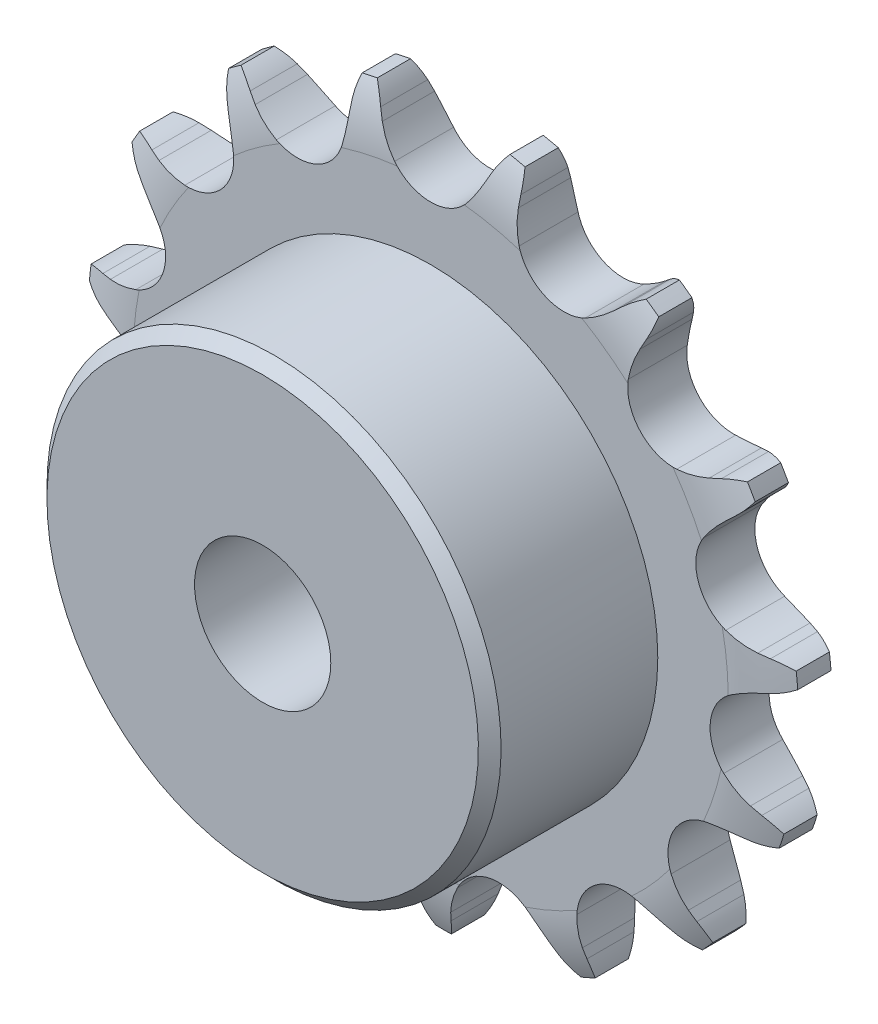
SolidWorks part; units mm, degrees
ref_plane "Front Plane" through (0, 0, 0) normal (0, 0, 1) x (1, 0, 0)
ref_plane "Top Plane" through (0, 0, 0) normal (0, 1, 0) x (1, 0, 0)
ref_plane "Right Plane" through (0, 0, 0) normal (1, 0, 0) x (0, 0, -1)
sketch "Sketch0" plane through (0, 0, 0) normal (0, 0, 1) x (1, 0, 0)
  line L0 (3, -14.1139) -> (0, 0) construction
  line L1 (0, 0) -> (8.4813, -11.6735) construction
  line L2 (0, 0) -> (-3, -14.1139) construction
  line L3 (3, -14.1139) -> (8.4813, -11.6735) construction
  line L4 (3, -14.1139) -> (-3, -14.1139) construction
  line L5 (5.4587, -13.8191) -> (5.1921, -13.4619)
  line L6 (3, -14.1139) -> (0, -14.7516) construction
  line L7 (0.6339, -14.8447) -> (0.7322, -14.4099)
  line L8 (0, -14.1139) -> (0, -15.9139) construction
  line L9 (4.2889, -12.5222) -> (0.9862, -16.6008) construction
  line L10 (0, 0) -> (0, -14.1139) construction
  line L11 (5.1921, -13.4619) -> (0.9862, -16.6008) construction
  line L12 (0, -15.9139) -> (0, -16.1712) construction
  line L13 (8.1159, -11.8362) -> (5.4587, -13.8191) construction
  circle A0 centre (0, 0) radius 15.9139 construction
  circle A1 centre (0, 0) radius 14.4292 construction
  arc A2 (-3.2007, -17.3745) -> (9.9908, -14.5706) centre (0, 0) ccw
  circle A3 centre (0, 0) radius 16.1712 construction
  circle A4 centre (3, -14.1139) radius 2 construction
  arc A7 (4.2889, -12.5222) -> (1.1751, -13.1841) centre (3, -14.1139) ccw
  circle A8 centre (3, -14.1139) radius 2.0481 construction
  arc A9 (5.4587, -13.8191) -> (9.9908, -14.5706) centre (8.1159, -11.8362) ccw
  arc A10 (5.1921, -13.4619) -> (4.2889, -12.5222) centre (0.9862, -16.6008) ccw
  arc A11 (0.6339, -14.8447) -> (-3.2007, -17.3745) centre (-2.6, -14.1139) cw
  arc A12 (0.7322, -14.4099) -> (1.1751, -13.1841) centre (5.8512, -15.5667) cw
  dimension "D1" = 2.0481
  dimension "R" = 2.0481
sketch "Sketch1" plane through (0, 0, 0) normal (1, 0, 0) x (0, 0, -1)
  line L0 (1.3, 0) -> (-1.3, 0)
  line L1 (-1.3, 0) -> (-1.3, 13.1014)
  line L2 (-1.3, 14.4292) -> (0, 14.4292) construction
  line L3 (-0.6, 15.9139) -> (0.6, 15.9139)
  line L5 (1.3, 13.1014) -> (1.3, 0)
  line L7 (0, 15.9139) -> (0, 0) construction
  line L8 (-1.3, 13.1014) -> (1.3, 13.1014) construction
  line L9 (0, 15.9139) -> (0, -15.9139) construction
  line L10 (-1.3, 13.1014) -> (-1.3, 15.9139) construction
  line L11 (-1.3, 15.9139) -> (-0.6, 15.9139) construction
  line L12 (0.6, 15.9139) -> (1.3, 15.9139) construction
  line L13 (1.3, 15.9139) -> (1.3, 13.1014) construction
  line L14 (0, 0) -> (-6.4008, 0) construction
  line L15 (-1.3, 14.4292) -> (-1.3, 10.3292) construction
  line L22 (1.3, 0) -> (-8.7, 0) construction
  line L24 (-1.3, 0) -> (-1.3, 10.3292) construction
  arc A0 (-0.6, 15.9139) -> (-1.3, 13.1014) centre (4.7, 13.1014) ccw
  arc A1 (0.6, 15.9139) -> (1.3, 13.1014) centre (-4.7, 13.1014) cw
  dimension "R" = 6
revolve "Revolve1" add sketch "Sketch1" angle 360 mid plane about L0
extrude "Cut-Extrude1" cut sketch "Sketch0" against normal through all and the other way through all
pattern_circular "CirPattern1" count 15 over 360 about axis through (0, 0, 0) along (0, 0, 1) of "Cut-Extrude1"
sketch "Sketch2" plane through (0, 0, 0) normal (0, 0, 1) x (1, 0, 0)
  circle A0 centre (0, 0) radius 3 construction
  circle A1 centre (0, 0) radius 10
  circle A2 centre (0, 0) radius 15.65 construction
  dimension "Bore" = 6
  dimension "Hub Dia." = 20
  dimension "OD" = 31.3
extrude "Boss-Extrude1" add sketch "Sketch2" along normal up to vertex (8.7 mm away) from surface at 1.3 starting at face at (0, 0, 1.3)
sketch "Sketch3" plane through (0, 0, 0) normal (0, 0, 1) x (1, 0, 0)
  circle A0 centre (0, 0) radius 3 construction
  circle A1 centre (0, 0) radius 3
extrude "Cut-Extrude2" cut sketch "Sketch3" along normal through all and the other way through all
sketch "Sketch4" plane through (0, 0, 0) normal (1, 0, 0) x (0, 0, -1)
  line L0 (-8.7, 10) -> (-8.7, 9.5)
  line L1 (-1.3, 15.9139) -> (-3.25, 15.9139)
  line L2 (-1.3, 15.9139) -> (-1.3, 10.3292)
  line L3 (-1.3, 10.3292) -> (-3.25, 10.3292)
  line L4 (-3.25, 15.9139) -> (-3.25, 10.3292)
  line L9 (-8.7, 9.5) -> (-8.2, 10)
  line L10 (-8.2, 10) -> (-8.7, 10)
  dimension "C" = 0.5
  dimension "D3" = 1.95
revolve "Cut-Revolve1" cut sketch "Sketch4" angle 360 mid plane about L22
sketch "Sketch5" plane through (0, 0, 0) normal (0, 0, 1) x (1, 0, 0)
  circle A0 centre (0, 0) radius 15.65 construction
  circle A1 centre (0, 0) radius 15.65
extrude "Cut-Extrude3" cut sketch "Sketch5" against normal through all and the other way through all flip side to cut
equation "\"360/N@Sketch0\" = 360/\"Teeth@CirPattern1\""
equation "\"Ds@Sketch0\" = 1.005 * \"Dr@Sketch0\" + ( 0.003 * 25.4 ) "
equation "\"R@Sketch0\" = 1/2 * \"Ds@Sketch0\""
equation "\"A@Sketch0\" = 35 +  ( 60 / \"Teeth@CirPattern1\" ) "
equation "\"B@Sketch0\" = 18 -  ( 56 / \"Teeth@CirPattern1\" )"
equation "\"ac@Sketch0\" = 0.8 * \"Dr@Sketch0\""
equation "\"ab@Sketch0\" = 1.4 * \"Dr@Sketch0\""
equation "\"J@Sketch0\" = 0.3 * \"Pitch@Sketch0\""
equation "\"D3@Sketch4\" = \"t@Sketch1\" * 3 / 4"
